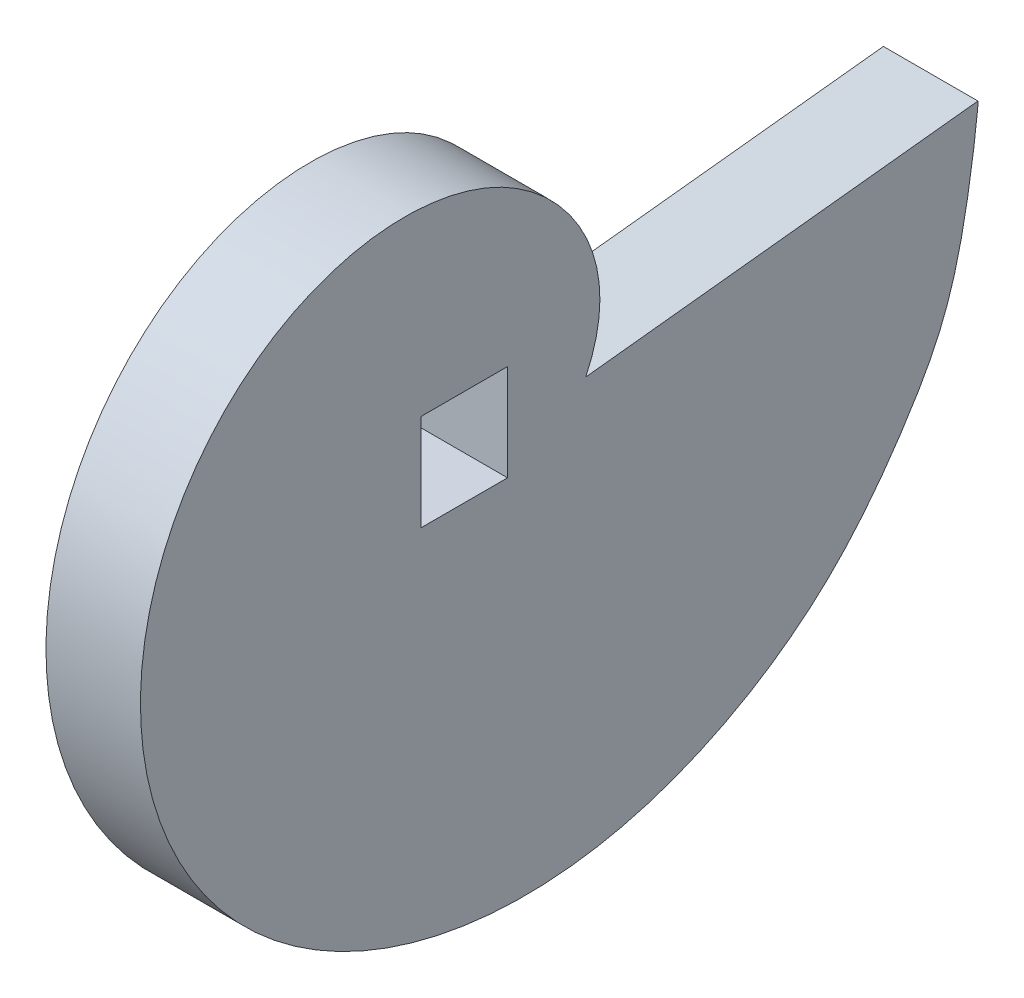
SolidWorks part; units mm, degrees
ref_plane "Front Plane" through (0, 0, 0) normal (1, 0, 0) x (0, 1, 0)
ref_plane "Top Plane" through (0, 0, 0) normal (0, 0, 1) x (0, 1, 0)
ref_plane "Right Plane" through (0, 0, 0) normal (0, 1, 0) x (-1, 0, 0)
sketch "Sketch1" plane through (0, 0, 0) normal (1, 0, 0) x (0, 0, -1)
  line L0 (0, 0) -> (9, 0) construction
  line L1 (9, 0) -> (9, 9) construction
  line L2 (9, 9) -> (0, 0) construction
  line L3 (9, 9) -> (2.636, 15.364) construction
  line L4 (2.636, 15.364) -> (0, 0) construction
  line L5 (2.636, 15.364) -> (-6.2343, 16.8859) construction
  line L6 (-6.2343, 16.8859) -> (0, 0) construction
  line L7 (-6.2343, 16.8859) -> (-14.6773, 13.7687) construction
  line L8 (-14.6773, 13.7687) -> (0, 0) construction
  line L9 (-14.6773, 13.7687) -> (-20.8348, 7.2048) construction
  line L10 (-20.8348, 7.2048) -> (0, 0) construction
  line L11 (-20.8348, 7.2048) -> (-23.7762, -1.301) construction
  line L12 (-23.7762, -1.301) -> (0, 0) construction
  line L13 (-23.7762, -1.301) -> (-23.2845, -10.2875) construction
  line L14 (-23.2845, -10.2875) -> (0, 0) construction
  line L15 (-23.2845, -10.2875) -> (-19.6473, -18.5198) construction
  line L16 (-19.6473, -18.5198) -> (0, 0) construction
  line L17 (-19.6473, -18.5198) -> (-13.474, -25.0689) construction
  line L18 (-13.474, -25.0689) -> (0, 0) construction
  line L19 (-13.474, -25.0689) -> (-5.5465, -29.3298) construction
  line L20 (-5.5465, -29.3298) -> (0, 0) construction
  line L21 (-5.5465, -29.3298) -> (3.2967, -31.0021) construction
  line L22 (3.2967, -31.0021) -> (0, 0) construction
  line L23 (3.2967, -31.0021) -> (12.2463, -30.0504) construction
  line L24 (12.2463, -30.0504) -> (0, 0) construction
  line L25 (12.2463, -30.0504) -> (20.5808, -26.6539) construction
  line L26 (20.5808, -26.6539) -> (0, 0) construction
  line L27 (20.5808, -26.6539) -> (27.7043, -21.1535) construction
  line L28 (27.7043, -21.1535) -> (0, 0) construction
  line L29 (27.7043, -21.1535) -> (33.1661, -14.0003) construction
  line L30 (33.1661, -14.0003) -> (0, 0) construction
  line L31 (33.1661, -14.0003) -> (36.6662, -5.7087) construction
  line L32 (36.6662, -5.7087) -> (0, 0) construction
  line L33 (36.6662, -5.7087) -> (38.0508, 3.1841) construction
  line L34 (38.0508, 3.1841) -> (0, 0) construction
  line L35 (9, 0) -> (38.0508, 3.1841)
  line L36 (9, 0) -> (38.0508, 3.1841) construction
  line L38 (-3.2084, 3.5702) -> (3.2084, 3.5702)
  line L39 (-3.2084, 3.5702) -> (-3.2084, -3.5702)
  line L40 (-3.2084, -3.5702) -> (3.2084, -3.5702)
  line L41 (3.2084, 3.5702) -> (3.2084, -3.5702)
  line L42 (-3.2084, 3.5702) -> (3.2084, -3.5702) construction
  line L43 (-3.2084, -3.5702) -> (3.2084, 3.5702) construction
  circle A0 centre (0, 0) radius 13 construction
  circle A1 centre (0, 0) radius 4.8
  spline S0 degree 3 poles (9, 0) (12.0197, 6.2595) (6.1427, 15.7991) (-6.3362, 17.6736) (-15.0842, 14.3532) (-21.3906, 7.5258) (-24.3623, -1.2274) (-23.8175, -10.4221) (-20.0746, -18.8095) (-13.7678, -25.4587) (-5.6983, -29.7691) (3.2817, -31.4436) (12.3519, -30.4694) (20.7884, -26.9816) (27.9793, -21.5277) (33.5206, -13.8284) (37.5044, -6.049) (38.6681, 8.5802) (37.3585, -1.2623) knots 0 0 0 0 0.114286 0.171429 0.228571 0.285714 0.342857 0.4 0.457143 0.514286 0.571429 0.628571 0.685714 0.742857 0.8 0.857143 0.914286 1 1 1 1
  dimension "D1" = 26
  dimension "D4" = 9.6
  dimension "D2" = 9
extrude "Boss-Extrude1" add sketch "Sketch1" along normal blind 7
